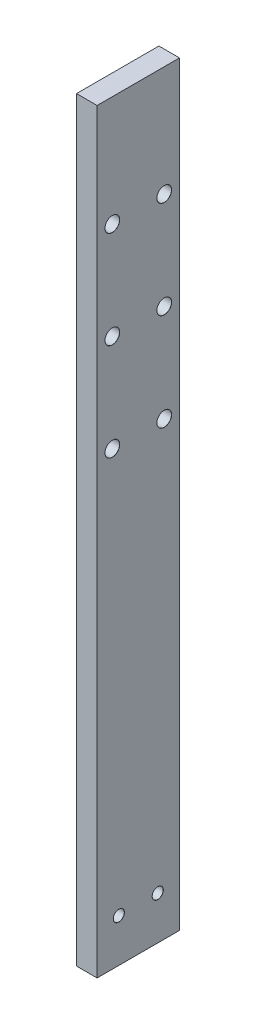
SolidWorks part; units mm, degrees
material "6061 Alloy"
ref_plane "Front" through (0, 0, 0) normal (0, 0, 1) x (1, 0, 0)
ref_plane "Top" through (0, 0, 0) normal (0, 1, 0) x (1, 0, 0)
ref_plane "Right" through (0, 0, 0) normal (1, 0, 0) x (0, 0, -1)
sketch "Sketch1" plane through (0, 0, 0) normal (1, 0, 0) x (0, 0, -1)
  line L1 (0, 0) -> (25.4, 0)
  line L2 (0, 0) -> (0, 232.968)
  line L3 (0, 232.968) -> (25.4, 232.968)
  line L4 (25.4, 0) -> (25.4, 232.968)
  dimension "D1" = 25.4
  dimension "D2" = 232.968
extrude "Boss-Extrude1" add sketch "Sketch1" along normal blind 6.35
hole_wizard "M3 Clearance Hole1" positions "Sketch2" profile "Sketch3" hole size "M3" standard "ANSI Metric"
sketch "Sketch2" plane through (6.35, 0, 0) normal (1, 0, 0) x (0, 0, -1)
  line L0 (50, 0) -> (-50, 0) construction
  line L1 (6.7, 13.3) -> (18.7, 13.3) construction
  line L3 (12.7, 13.3) -> (12.7, 0) construction
  line L4 (0, 0) -> (25.4, 0) construction
  point P0 (6.7, 13.3)
  point P2 (18.7, 13.3)
  dimension "D1" = 12
  dimension "D2" = 13.3
sketch "Sketch3" plane through (6.35, 13.3, -6.7) normal (0, 1, 0) x (0, 0, -1)
  line L0 (0, 0) -> (0, 8.5145)
  line L1 (0, 8.5145) -> (1.7, 7.493)
  line L2 (1.7, 7.493) -> (1.7, 0.021)
  line L3 (1.7, 0.021) -> (1.725, 0)
  line L5 (1.725, 0) -> (0, 0)
  line L6 (-1.7, 0.021) -> (-1.725, 0) construction
  line L10 (0, 8.5145) -> (-1.7, 7.493) construction
  line L11 (0, -6.35) -> (0, 107.95) construction
  dimension "Hole Dia." = 3.4
  dimension "Hole Depth" = 7.493
  dimension "Near C'Sink Dia." = 3.45
  dimension "Near C'Sink Angle" = 100
  dimension "Drill Angle" = 118
hole_wizard "M4 Clearance Hole1" positions "Sketch4" profile "Sketch5" hole size "M4" standard "ANSI Metric"
sketch "Sketch4" plane through (6.35, 0, 0) normal (1, 0, 0) x (0, 0, -1)
  line L0 (25.4, 232.968) -> (0, 232.968) construction
  line L1 (20.7, 198.968) -> (4.7, 198.968) construction
  line L2 (4.7, 198.968) -> (12.7, 198.968) construction
  line L3 (12.7, 198.968) -> (12.7, 232.968) construction
  point P0 (4.7, 198.968)
  point P2 (4.7, 168.968)
  point P4 (4.7, 138.968)
  point P6 (20.7, 138.968)
  point P8 (20.7, 168.968)
  point P10 (20.7, 198.968)
  dimension "D1" = 94
  dimension "D2" = 30
  dimension "D3" = 30
  dimension "D4" = 16
sketch "Sketch5" plane through (6.35, 198.968, -4.7) normal (0, 1, 0) x (0, 0, -1)
  line L0 (0, 0) -> (0, 11.4519)
  line L1 (0, 11.4519) -> (2.25, 10.1)
  line L2 (2.25, 10.1) -> (2.25, 0.021)
  line L3 (2.25, 0.021) -> (2.275, 0)
  line L5 (2.275, 0) -> (0, 0)
  line L6 (-2.25, 0.021) -> (-2.275, 0) construction
  line L10 (0, 11.4519) -> (-2.25, 10.1) construction
  line L11 (0, -6.35) -> (0, 107.95) construction
  dimension "Hole Dia." = 4.5
  dimension "Hole Depth" = 10.1
  dimension "Near C'Sink Dia." = 4.55
  dimension "Near C'Sink Angle" = 100
  dimension "Drill Angle" = 118
